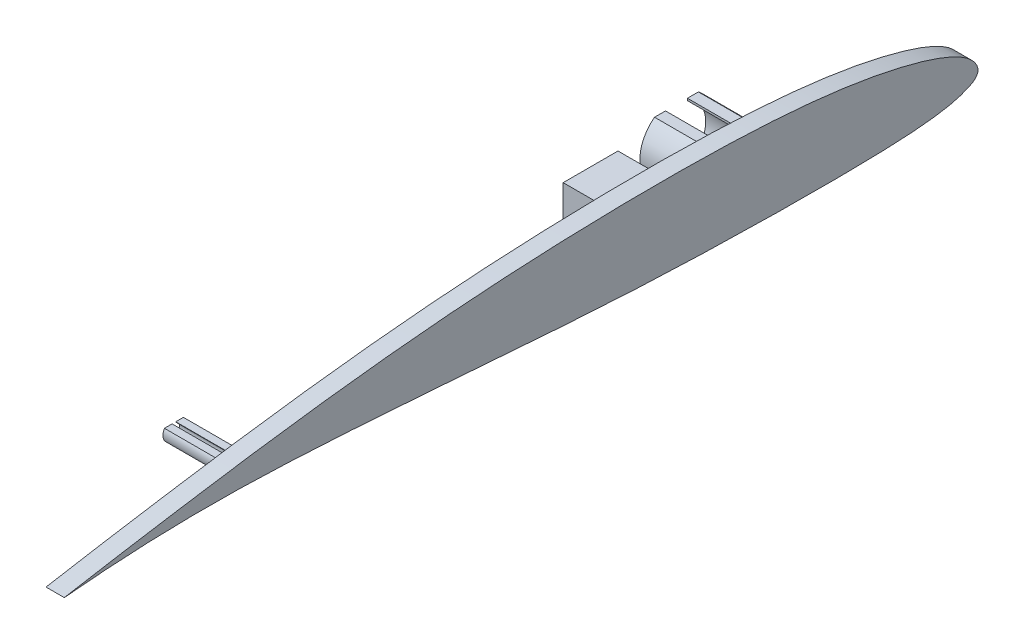
SolidWorks part; units mm, degrees
material "ABS generico"
ref_plane "Piano frontale" through (0, 0, 0) normal (0, 0, 1) x (1, 0, 0)
ref_plane "Piano superiore" through (0, 0, 0) normal (0, 1, 0) x (1, 0, 0)
ref_plane "Piano destro" through (0, 0, 0) normal (1, 0, 0) x (0, 0, -1)
curve "Curva1"
  spline degree 3 poles (0, 0.1724, 248.285) (0, -0.053, 250.4273) (0, 0.2462, 248.3284) (0, 0.5529, 246.6445) (0, 1.2459, 242.6221) (0, 2.0989, 237.7464) (0, 3.1818, 231.3634) (0, 4.2933, 223.9772) (0, 5.7312, 215.5604) (0, 7.1315, 206.3004) (0, 8.6324, 196.1631) (0, 10.1162, 185.3524) (0, 11.5493, 173.9891) (0, 12.8816, 162.1914) (0, 14.0593, 150.0724) (0, 15.0523, 137.7438) (0, 15.8256, 125.3116) (0, 16.3834, 112.8888) (0, 16.7267, 100.597) (0, 16.8648, 88.5669) (0, 16.792, 76.9314) (0, 16.4941, 65.8165) (0, 15.9609, 55.3329) (0, 15.1594, 45.573) (0, 14.0978, 36.6074) (0, 12.7884, 28.4972) (0, 11.2839, 21.2988) (0, 9.6413, 15.0749) (0, 7.9136, 9.8809) (0, 6.1182, 5.7699) (0, 4.2384, 2.7289) (0, 2.3057, 0.8126) (0, 0.7927, 0.0312) (0, -0.4105, -0.0213) (0, -1.7115, 0.4949) (0, -2.8658, 2.6253) (0, -4.0404, 5.6977) (0, -4.9287, 10.0719) (0, -5.5974, 15.6262) (0, -6.0122, 22.4122) (0, -6.265, 30.3619) (0, -6.3814, 39.3972) (0, -6.3554, 49.3987) (0, -6.2185, 60.2453) (0, -5.9476, 71.8018) (0, -5.5368, 83.9408) (0, -4.9386, 96.5461) (0, -4.1527, 109.5201) (0, -3.2196, 122.7671) (0, -2.1909, 136.1764) (0, -1.148, 149.6158) (0, -0.1602, 162.9314) (0, 0.706, 175.9537) (0, 1.3896, 188.4999) (0, 1.8332, 200.3712) (0, 1.9676, 211.3376) (0, 1.8232, 221.1842) (0, 1.4973, 229.6804) (0, 1.0741, 236.8065) (0, 0.6857, 242.1894) (0, 0.3087, 246.5181) (0, 0.1724, 248.285) (0, -0.053, 250.4273) (0, 0.2462, 248.3284) knots -0.014202 -0.006329 -0.001589 0 0.001576 0.006211 0.01368 0.023764 0.036307 0.051658 0.068045 0.086769 0.107053 0.128647 0.151303 0.174786 0.19886 0.223309 0.247929 0.272522 0.296848 0.320648 0.343669 0.365658 0.3864 0.405741 0.423561 0.439779 0.454311 0.467034 0.477831 0.486643 0.493542 0.498786 0.50271 0.50309 0.505896 0.510322 0.516831 0.525521 0.536535 0.549945 0.565696 0.583577 0.603379 0.624844 0.647727 0.671743 0.696673 0.722357 0.748609 0.77521 0.801891 0.828329 0.854175 0.879074 0.902636 0.924421 0.943939 0.960827 0.974827 0.985798 0.993671 0.998411 1 1.001576 1.006211 1.01368 periodic
sketch "Schizzo1" plane through (0, 0, 0) normal (1, 0, 0) x (0, 0, -1)
  line L0 (-250, 0) -> (0.0001, 0.0174) construction
  line L1 (0.0001, 0.0174) -> (-0.0034, 50.0174) construction
  line L2 (-62.4999, 16.3096) -> (-62.4999, -6.155) construction
  line L4 (-78.4999, 10.0773) -> (-93.4999, 10.0773) construction
  line L5 (-78.4999, 10.0773) -> (-78.4999, 0.0773) construction
  line L6 (-78.4999, 0.0773) -> (-93.4999, 0.0773) construction
  line L7 (-93.4999, 10.0773) -> (-93.4999, 0.0773) construction
  circle A0 centre (-62.4999, 5.0773) radius 8 construction
  spline S0 degree 3 poles (-248.3284, 0.2462) (-250.4273, -0.053) (-248.285, 0.1724) (-246.5181, 0.3087) (-242.1894, 0.6857) (-236.8065, 1.0741) (-229.6804, 1.4973) (-221.1842, 1.8232) (-211.3376, 1.9676) (-200.3712, 1.8332) (-188.4999, 1.3896) (-175.9537, 0.706) (-162.9314, -0.1602) (-149.6158, -1.148) (-136.1764, -2.1909) (-122.7671, -3.2196) (-109.5201, -4.1527) (-96.5461, -4.9386) (-83.9408, -5.5368) (-71.8018, -5.9476) (-60.2453, -6.2185) (-49.3987, -6.3554) (-39.3972, -6.3814) (-30.3619, -6.265) (-22.4122, -6.0122) (-15.6262, -5.5974) (-10.0719, -4.9287) (-5.6977, -4.0404) (-2.6253, -2.8658) (-0.4949, -1.7115) (0.0213, -0.4105) (-0.0312, 0.7927) (-0.8126, 2.3057) (-2.7289, 4.2384) (-5.7699, 6.1182) (-9.8809, 7.9136) (-15.0749, 9.6413) (-21.2988, 11.2839) (-28.4972, 12.7884) (-36.6074, 14.0978) (-45.573, 15.1594) (-55.3329, 15.9609) (-65.8165, 16.4941) (-76.9314, 16.792) (-88.5669, 16.8648) (-100.597, 16.7267) (-112.8888, 16.3834) (-125.3116, 15.8256) (-137.7438, 15.0523) (-150.0724, 14.0593) (-162.1914, 12.8816) (-173.9891, 11.5493) (-185.3524, 10.1162) (-196.1631, 8.6324) (-206.3004, 7.1315) (-215.5604, 5.7312) (-223.9772, 4.2933) (-231.3634, 3.1818) (-237.7464, 2.0989) (-242.6221, 1.2459) (-246.6445, 0.5529) (-248.3284, 0.2462) (-250.4273, -0.053) (-248.285, 0.1724) knots -0.01368 -0.006211 -0.001576 0 0.001589 0.006329 0.014202 0.025173 0.039173 0.056061 0.075579 0.097364 0.120926 0.145825 0.171671 0.198109 0.22479 0.251391 0.277643 0.303327 0.328257 0.352273 0.375156 0.396621 0.416423 0.434304 0.450055 0.463465 0.474479 0.483169 0.489678 0.494104 0.49691 0.49729 0.501214 0.506458 0.513357 0.522169 0.532966 0.545689 0.560221 0.576439 0.594259 0.6136 0.634342 0.656331 0.679352 0.703152 0.727478 0.752071 0.776691 0.80114 0.825214 0.848697 0.871353 0.892947 0.913231 0.931955 0.948342 0.963693 0.976236 0.98632 0.993789 0.998424 1 1.001589 1.006329 1.014202 only from (-250, 0) to (-250, 0) construction
  spline S1 degree 3 poles (-248.3284, 0.2462) (-250.4273, -0.053) (-248.285, 0.1724) (-246.5181, 0.3087) (-242.1894, 0.6857) (-236.8065, 1.0741) (-229.6804, 1.4973) (-221.1842, 1.8232) (-211.3376, 1.9676) (-200.3712, 1.8332) (-188.4999, 1.3896) (-175.9537, 0.706) (-162.9314, -0.1602) (-149.6158, -1.148) (-136.1764, -2.1909) (-122.7671, -3.2196) (-109.5201, -4.1527) (-96.5461, -4.9386) (-83.9408, -5.5368) (-71.8018, -5.9476) (-60.2453, -6.2185) (-49.3987, -6.3554) (-39.3972, -6.3814) (-30.3619, -6.265) (-22.4122, -6.0122) (-15.6262, -5.5974) (-10.0719, -4.9287) (-5.6977, -4.0404) (-2.6253, -2.8658) (-0.4949, -1.7115) (0.0213, -0.4105) (-0.0312, 0.7927) (-0.8126, 2.3057) (-2.7289, 4.2384) (-5.7699, 6.1182) (-9.8809, 7.9136) (-15.0749, 9.6413) (-21.2988, 11.2839) (-28.4972, 12.7884) (-36.6074, 14.0978) (-45.573, 15.1594) (-55.3329, 15.9609) (-65.8165, 16.4941) (-76.9314, 16.792) (-88.5669, 16.8648) (-100.597, 16.7267) (-112.8888, 16.3834) (-125.3116, 15.8256) (-137.7438, 15.0523) (-150.0724, 14.0593) (-162.1914, 12.8816) (-173.9891, 11.5493) (-185.3524, 10.1162) (-196.1631, 8.6324) (-206.3004, 7.1315) (-215.5604, 5.7312) (-223.9772, 4.2933) (-231.3634, 3.1818) (-237.7464, 2.0989) (-242.6221, 1.2459) (-246.6445, 0.5529) (-248.3284, 0.2462) (-250.4273, -0.053) (-248.285, 0.1724) knots -0.01368 -0.006211 -0.001576 0 0.001589 0.006329 0.014202 0.025173 0.039173 0.056061 0.075579 0.097364 0.120926 0.145825 0.171671 0.198109 0.22479 0.251391 0.277643 0.303327 0.328257 0.352273 0.375156 0.396621 0.416423 0.434304 0.450055 0.463465 0.474479 0.483169 0.489678 0.494104 0.49691 0.49729 0.501214 0.506458 0.513357 0.522169 0.532966 0.545689 0.560221 0.576439 0.594259 0.6136 0.634342 0.656331 0.679352 0.703152 0.727478 0.752071 0.776691 0.80114 0.825214 0.848697 0.871353 0.892947 0.913231 0.931955 0.948342 0.963693 0.976236 0.98632 0.993789 0.998424 1 1.001589 1.006329 1.014202 only from (-250, 0) to (-250, 0)
  point P11 (-78.4999, 5.0773)
  dimension "D3" = 16
  dimension "D1" = 50
  dimension "D2" = 62.5
  dimension "D4" = 15
  dimension "D5" = 10
  dimension "D6" = 16
extrude "CorpoFoam" add sketch "Schizzo1" along normal blind 5
sketch "Schizzo3" plane through (5, 0, 0) normal (1, 0, 0) x (0, 0, -1)
  line L0 (-200, 8.0593) -> (-200, 1.7757) construction
  line L1 (-200.5, 6.4175) -> (-199.5, 3.4175) construction
  line L2 (-197.4019, 6.4175) -> (-199.5, 6.4175)
  line L4 (-197.4019, 3.4175) -> (-199.5, 3.4175)
  line L7 (-200.5, 6.4175) -> (-200.5, 6.3317)
  line L9 (-199.5, 6.4175) -> (-199.5, 6.3317)
  line L10 (-199.5, 6.4175) -> (-200.5, 3.4175) construction
  line L11 (-200.5, 6.4175) -> (-202.5981, 6.4175)
  line L12 (-200.5, 3.4175) -> (-202.5981, 3.4175)
  line L13 (-199.5, 3.5033) -> (-199.5, 3.4175)
  line L14 (-200.5, 3.5033) -> (-200.5, 3.4175)
  arc A0 (-200.5, 6.3317) -> (-200.5, 3.5033) centre (-200, 4.9175) ccw
  arc A1 (-202.5981, 6.4175) -> (-202.5981, 3.4175) centre (-200, 4.9175) ccw
  arc A2 (-197.4019, 3.4175) -> (-197.4019, 6.4175) centre (-200, 4.9175) ccw
  arc A3 (-199.5, 3.5033) -> (-199.5, 6.3317) centre (-200, 4.9175) ccw
  spline S0 degree 3 poles (-248.3284, 0.2462) (-250.4273, -0.053) (-248.285, 0.1724) (-246.5181, 0.3087) (-242.1894, 0.6857) (-236.8065, 1.0741) (-229.6804, 1.4973) (-221.1842, 1.8232) (-211.3376, 1.9676) (-200.3712, 1.8332) (-188.4999, 1.3896) (-175.9537, 0.706) (-162.9314, -0.1602) (-149.6158, -1.148) (-136.1764, -2.1909) (-122.7671, -3.2196) (-109.5201, -4.1527) (-96.5461, -4.9386) (-83.9408, -5.5368) (-71.8018, -5.9476) (-60.2453, -6.2185) (-49.3987, -6.3554) (-39.3972, -6.3814) (-30.3619, -6.265) (-22.4122, -6.0122) (-15.6262, -5.5974) (-10.0719, -4.9287) (-5.6977, -4.0404) (-2.6253, -2.8658) (-0.4949, -1.7115) (0.0213, -0.4105) (-0.0312, 0.7927) (-0.8126, 2.3057) (-2.7289, 4.2384) (-5.7699, 6.1182) (-9.8809, 7.9136) (-15.0749, 9.6413) (-21.2988, 11.2839) (-28.4972, 12.7884) (-36.6074, 14.0978) (-45.573, 15.1594) (-55.3329, 15.9609) (-65.8165, 16.4941) (-76.9314, 16.792) (-88.5669, 16.8648) (-100.597, 16.7267) (-112.8888, 16.3834) (-125.3116, 15.8256) (-137.7438, 15.0523) (-150.0724, 14.0593) (-162.1914, 12.8816) (-173.9891, 11.5493) (-185.3524, 10.1162) (-196.1631, 8.6324) (-206.3004, 7.1315) (-215.5604, 5.7312) (-223.9772, 4.2933) (-231.3634, 3.1818) (-237.7464, 2.0989) (-242.6221, 1.2459) (-246.6445, 0.5529) (-248.3284, 0.2462) (-250.4273, -0.053) (-248.285, 0.1724) knots -0.01368 -0.006211 -0.001576 0 0.001589 0.006329 0.014202 0.025173 0.039173 0.056061 0.075579 0.097364 0.120926 0.145825 0.171671 0.198109 0.22479 0.251391 0.277643 0.303327 0.328257 0.352273 0.375156 0.396621 0.416423 0.434304 0.450055 0.463465 0.474479 0.483169 0.489678 0.494104 0.49691 0.49729 0.501214 0.506458 0.513357 0.522169 0.532966 0.545689 0.560221 0.576439 0.594259 0.6136 0.634342 0.656331 0.679352 0.703152 0.727478 0.752071 0.776691 0.80114 0.825214 0.848697 0.871353 0.892947 0.913231 0.931955 0.948342 0.963693 0.976236 0.98632 0.993789 0.998424 1 1.001589 1.006329 1.014202 only from (-250, 0) to (-250, 0) construction
  dimension "D1" = 3
  dimension "D2" = 6
  dimension "D3" = 50
  dimension "D4" = 1
extrude "PernoAggancioAlettone" add sketch "Schizzo3" against normal blind 20
sketch "Schizzo4" plane through (0, 0, 0) normal (-1, 0, 0) x (0, 0, 1)
  line L0 (80.4999, 8.0773) -> (80.4999, 2.0773)
  line L1 (56.4999, 13.0773) -> (59.4999, 13.0773)
  line L3 (56.4999, -2.9227) -> (59.4999, -2.9227)
  line L5 (78.4999, 10.0773) -> (93.4999, 10.0773)
  line L6 (78.4999, 10.0773) -> (78.4999, 0.0773)
  line L7 (78.4999, 0.0773) -> (93.4999, 0.0773)
  line L8 (93.4999, 10.0773) -> (93.4999, 0.0773)
  line L9 (80.4999, 2.0773) -> (91.4999, 2.0773)
  line L10 (91.4999, 8.0773) -> (91.4999, 2.0773)
  line L11 (80.4999, 8.0773) -> (91.4999, 8.0773)
  line L12 (59.4999, 13.0773) -> (65.4999, -2.9227) construction
  line L14 (59.4999, 13.0773) -> (59.4999, 12.4935)
  line L16 (65.4999, 13.0773) -> (65.4999, 12.4935)
  line L17 (65.4999, 13.0773) -> (68.4999, 13.0773)
  line L18 (65.4999, -2.3389) -> (65.4999, -2.9227)
  line L19 (59.4999, -2.3389) -> (59.4999, -2.9227)
  line L20 (65.4999, -2.9227) -> (68.4999, -2.9227)
  arc A0 (59.4999, 12.4935) -> (59.4999, -2.3389) centre (62.4999, 5.0773) ccw
  arc A1 (56.4999, 13.0773) -> (56.4999, -2.9227) centre (62.4999, 5.0773) ccw
  arc A3 (68.4999, -2.9227) -> (68.4999, 13.0773) centre (62.4999, 5.0773) ccw
  arc A4 (65.4999, -2.3389) -> (65.4999, 12.4935) centre (62.4999, 5.0773) ccw
  dimension "D1" = 20
  dimension "D2" = 2
  dimension "D3" = 6
  dimension "D4" = 3
extrude "Estrusione-Estrusione1" add sketch "Schizzo4" along normal blind 15
